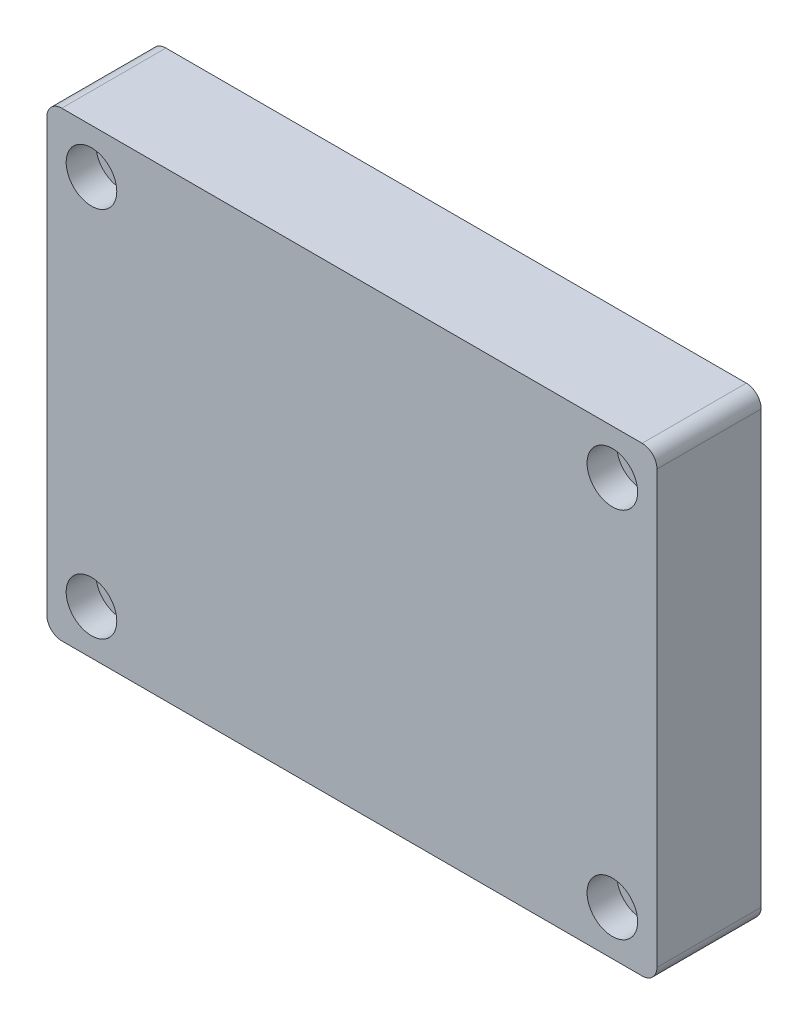
SolidWorks part; units mm, degrees
ref_plane "前视基准面" through (0, 0, 0) normal (0, 0, 1) x (1, 0, 0)
ref_plane "上视基准面" through (0, 0, 0) normal (0, 1, 0) x (1, 0, 0)
ref_plane "右视基准面" through (0, 0, 0) normal (1, 0, 0) x (0, 0, -1)
sketch "草图1" plane through (0, 0, 0) normal (0, 0, 1) x (1, 0, 0)
  line L1 (-20.5, 15.5) -> (20.5, 15.5)
  line L2 (-20.5, 15.5) -> (-20.5, -15.5)
  line L3 (-20.5, -15.5) -> (20.5, -15.5)
  line L4 (20.5, 15.5) -> (20.5, -15.5)
  line L5 (-20.5, 15.5) -> (20.5, -15.5) construction
  line L6 (-20.5, -15.5) -> (20.5, 15.5) construction
  point P0 (0, 0)
extrude "拉伸-薄壁1" add sketch "草图1" along normal blind 4 thin
sketch "草图2" plane through (0, 0, 4) normal (0, 0, 1) x (1, 0, 0)
  line L1 (-20.5, 15.5) -> (20.5, 15.5)
  line L2 (-20.5, 15.5) -> (-20.5, -15.5)
  line L3 (-20.5, -15.5) -> (20.5, -15.5)
  line L4 (20.5, 15.5) -> (20.5, -15.5)
  line L5 (-20.5, 15.5) -> (20.5, -15.5) construction
  line L6 (-20.5, -15.5) -> (20.5, 15.5) construction
  point P0 (0, 0)
extrude "凸台-拉伸1" add sketch "草图2" along normal blind 1 contours L2 L1 L4 L3
sketch "草图3" plane through (0, 0, 0) normal (0, 0, -1) x (-1, 0, 0)
  line L0 (15.5, 10.5) -> (15.5, 15.5) construction
  line L1 (-20.5, 15.5) -> (20.5, 15.5) construction
  line L2 (15.5, 15.5) -> (20.5, 15.5) construction
  line L3 (20.5, 15.5) -> (20.5, 10.5) construction
  line L4 (20.5, 15.5) -> (20.5, -15.5) construction
  line L5 (20.5, 10.5) -> (15.5, 10.5) construction
  line L6 (0, 15.5) -> (0, -15.5) construction
  line L7 (20.5, -15.5) -> (-20.5, -15.5) construction
  line L8 (-20.5, 0) -> (20.5, 0) construction
  line L9 (-20.5, -15.5) -> (-20.5, 15.5) construction
  circle A0 centre (17.5, 12.5) radius 1.7
  circle A1 centre (-17.5, 12.5) radius 1.7
  circle A2 centre (17.5, -12.5) radius 1.7
  circle A3 centre (-17.5, -12.5) radius 1.7
  dimension "D1" = 3
  dimension "D2" = 3
extrude "切除-拉伸1" cut sketch "草图3" along normal blind 2 from surface at -5 starting at face at (0, 0, 5)
sketch "草图4" plane through (0, 0, 3) normal (0, 0, 1) x (1, 0, 0)
  line L0 (0, 15.5) -> (0, -15.5) construction
  line L1 (20.5, 15.5) -> (-20.5, 15.5) construction
  line L2 (-20.5, -15.5) -> (20.5, -15.5) construction
  line L3 (-20.5, 0) -> (20.5, 0) construction
  line L4 (-20.5, 15.5) -> (-20.5, -15.5) construction
  line L5 (20.5, -15.5) -> (20.5, 15.5) construction
  circle A0 centre (17.5, 12.5) radius 0.7
  circle A1 centre (-17.5, 12.5) radius 0.7
  circle A2 centre (17.5, -12.5) radius 0.7
  circle A3 centre (-17.5, -12.5) radius 0.7
extrude "切除-拉伸2" cut sketch "草图4" against normal through all
fillet "圆角1" radius 1 4 edges at (20.5, -15.5, 2.5) (-20.5, -15.5, 2.5) (-20.5, 15.5, 2.5) (20.5, 15.5, 2.5)
sketch "草图5" plane through (0, 0, 0) normal (0, 0, -1) x (-1, 0, 0)
  line L0 (-15.5, 10.5) -> (-15.5, 12.5)
  line L5 (-17.5, 10.5) -> (-19, 10.5)
  line L6 (-19, 10.5) -> (-19, -10.5)
  line L8 (15.5, 12.5) -> (15.5, 10.5)
  line L9 (15.5, 10.5) -> (17.5, 10.5)
  line L11 (17.5, -10.5) -> (15.5, -10.5)
  line L12 (15.5, -10.5) -> (15.5, -12.5)
  line L14 (-15.5, -12.5) -> (-15.5, -10.5)
  line L15 (-15.5, -10.5) -> (-17.5, -10.5)
  line L17 (-17.5, 10.5) -> (-15.5, 10.5)
  line L18 (-19, -10.5) -> (-17.5, -10.5)
  line L19 (-15.5, -12.5) -> (-15.5, -14)
  line L20 (-15.5, -14) -> (15.5, -14)
  line L21 (15.5, -14) -> (15.5, -12.5)
  line L22 (-15.5, 12.5) -> (-15.5, 14)
  line L23 (-15.5, 14) -> (15.5, 14)
  line L24 (15.5, 14) -> (15.5, 12.5)
  line L25 (17.5, 10.5) -> (19, 10.5)
  line L26 (19, 10.5) -> (19, -10.5)
  line L27 (19, -10.5) -> (17.5, -10.5)
  point P0 (0, 0)
extrude "切除-拉伸3" cut sketch "草图5" against normal blind 4
sketch "草图6" plane through (20.5, 0, 0) normal (1, 0, 0) x (0, 0, -1)
  line L0 (0, 0) -> (-1, 0) construction
  line L1 (-1, 0) -> (-1, 15.5) construction
  line L2 (-5, 15.5) -> (0, 15.5) construction
  line L3 (-1, 15.5) -> (-1, -15.5) construction
  line L4 (0, -15.5) -> (-5, -15.5) construction
  line L5 (-1, 0) -> (-2.6, 0) construction
  line L6 (-2.6, -3.5) -> (-2.6, 3.5) construction
  line L7 (-4.3, -3.5) -> (-4.3, 3.5)
  line L8 (-0.9, -3.5) -> (-0.9, 3.5)
  line L9 (0, -0.0078) -> (-5, -0.0078) construction
  line L10 (0, -14.5) -> (0, 14.5) construction
  arc A0 (-4.3, -3.5) -> (-0.9, -3.5) centre (-2.6, -3.5) ccw
  arc A1 (-0.9, 3.5) -> (-4.3, 3.5) centre (-2.6, 3.5) ccw
  point P12 (-2.6, 0)
extrude "切除-拉伸4" [suppressed] cut sketch "草图6" against normal blind 5
sketch "草图7" plane through (0, 0, 0) normal (0, 0, -1) x (-1, 0, 0)
  line L0 (-20.5, 14.5) -> (-20.5, -14.5)
  line L1 (-19.5, 15.5) -> (19.5, 15.5)
  line L2 (20.5, 14.5) -> (20.5, -14.5)
  line L3 (19.5, -15.5) -> (-19.5, -15.5)
  line L4 (19.5, -15.5) -> (-19.5, -15.5) construction
  line L5 (-19.5, 13.5) -> (-19.5, -13.5)
  line L6 (-18.5, -14.5) -> (18.5, -14.5)
  line L7 (19.5, -13.5) -> (19.5, 13.5)
  line L8 (18.5, 14.5) -> (-18.5, 14.5)
  arc A0 (-20.5, -14.5) -> (-19.5, -15.5) centre (-19.5, -14.5) ccw construction
  arc A1 (-19.5, 15.5) -> (-20.5, 14.5) centre (-19.5, 14.5) ccw
  arc A2 (20.5, 14.5) -> (19.5, 15.5) centre (19.5, 14.5) ccw
  arc A3 (19.5, -15.5) -> (20.5, -14.5) centre (19.5, -14.5) ccw
  arc A4 (-20.5, -14.5) -> (-19.5, -15.5) centre (-19.5, -14.5) ccw
  arc A5 (18.5, 14.5) -> (19.5, 13.5) centre (18.5, 13.5) cw
  arc A6 (19.5, -13.5) -> (18.5, -14.5) centre (18.5, -13.5) cw
  arc A7 (-18.5, -14.5) -> (-19.5, -13.5) centre (-18.5, -13.5) cw
  arc A8 (-19.5, 13.5) -> (-18.5, 14.5) centre (-18.5, 13.5) cw
  dimension "D1" = 1
  dimension "D2" = 1
  dimension "D3" = 1
  dimension "D4" = 1
  dimension "D5" = 1
extrude "凸台-拉伸2" add sketch "草图7" along normal blind 2
